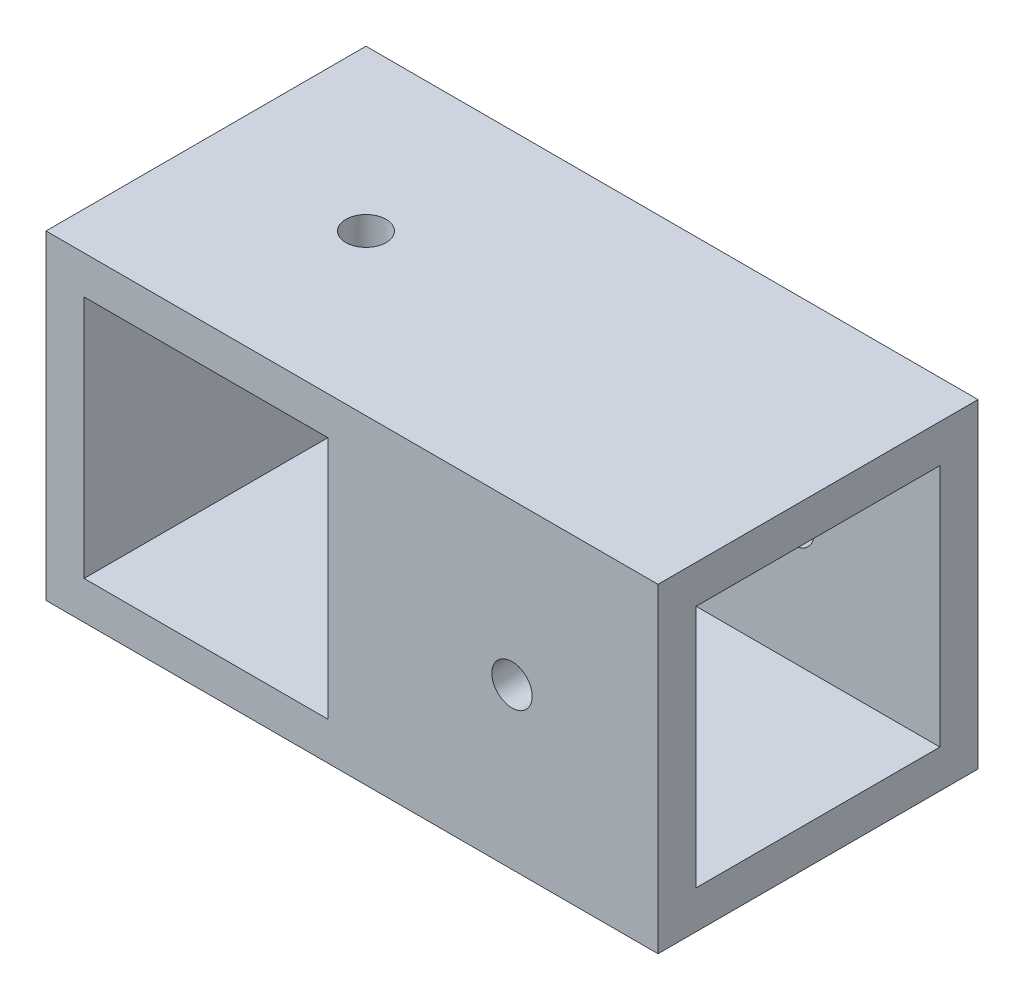
SolidWorks part; units mm, degrees
ref_plane "Front Plane" through (0, 0, 0) normal (0, 0, 1) x (1, 0, 0)
ref_plane "Top Plane" through (0, 0, 0) normal (0, 1, 0) x (1, 0, 0)
ref_plane "Right Plane" through (0, 0, 0) normal (1, 0, 0) x (0, 0, -1)
sketch "Sketch1" plane through (0, 0, 0) normal (0, 0, 1) x (1, 0, 0)
  line L0 (-12.6, 12.6) -> (12.6, 12.6)
  line L1 (-9.6, 9.6) -> (9.6, 9.6)
  line L2 (-9.6, 9.6) -> (-9.6, -9.6)
  line L3 (-9.6, -9.6) -> (9.6, -9.6)
  line L4 (9.6, 9.6) -> (9.6, -9.6)
  line L5 (-9.6, 9.6) -> (9.6, -9.6) construction
  line L6 (-9.6, -9.6) -> (9.6, 9.6) construction
  line L7 (12.6, 12.6) -> (12.6, -12.6)
  line L8 (-12.6, -12.6) -> (12.6, -12.6)
  line L9 (-12.6, 12.6) -> (-12.6, -12.6)
  point P0 (0, 0)
  dimension "D1" = 19.2
  dimension "D2" = 19.2
  dimension "D3" = 3
extrude "Boss-Extrude1" add sketch "Sketch1" along normal blind 25.2
sketch "Sketch3" plane through (12.6, 0, 0) normal (1, 0, 0) x (0, 0, -1)
  line L0 (-22.2, 9.6) -> (-22.2, -9.6)
  line L1 (-25.2, 12.6) -> (0, 12.6)
  line L2 (-25.2, 12.6) -> (-25.2, -12.6)
  line L3 (-25.2, -12.6) -> (0, -12.6)
  line L4 (0, 12.6) -> (0, -12.6)
  line L5 (-22.2, -9.6) -> (-3, -9.6)
  line L6 (-3, 9.6) -> (-3, -9.6)
  line L7 (-22.2, 9.6) -> (-3, 9.6)
  dimension "D1" = 3
extrude "Boss-Extrude2" add sketch "Sketch3" along normal blind 23
sketch "Sketch4" plane through (0, -9.6, 0) normal (0, 1, 0) x (1, 0, 0)
  line L0 (-9.6, 0) -> (9.6, -25.2) construction
  circle A0 centre (0, -12.6) radius 1.5875
  dimension "D1" = 3.175
extrude "Cut-Extrude1" cut sketch "Sketch4" against normal through all and the other way through all
sketch "Sketch5" plane through (0, 0, 3) normal (0, 0, 1) x (1, 0, 0)
  line L0 (12.6, 9.6) -> (35.6, -9.6) construction
  circle A0 centre (24.1, 0) radius 1.5875
  dimension "D1" = 3.175
extrude "Cut-Extrude2" cut sketch "Sketch5" along normal through all and the other way through all
